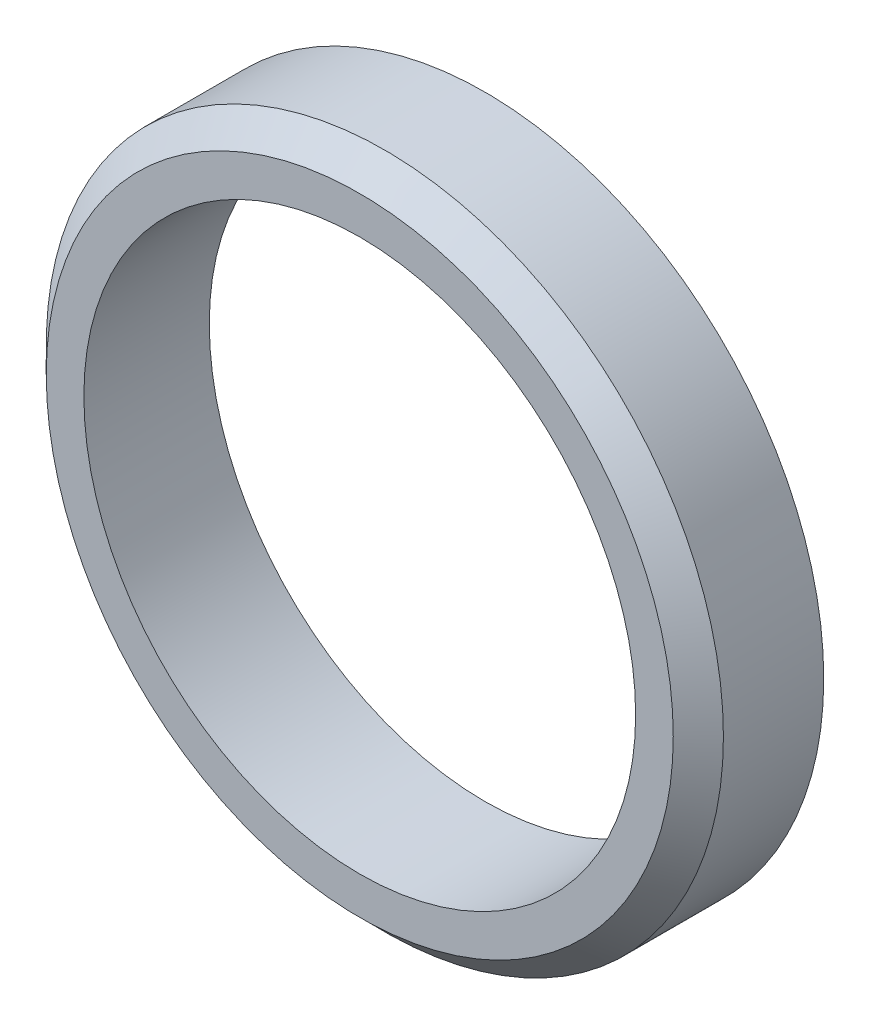
SolidWorks part; units mm, degrees
ref_plane "Спереди" through (0, 0, 0) normal (0, 0, 1) x (1, 0, 0)
ref_plane "Сверху" through (0, 0, 0) normal (0, 1, 0) x (1, 0, 0)
ref_plane "Справа" through (0, 0, 0) normal (1, 0, 0) x (0, 0, -1)
sketch "Эскиз1" plane through (0, 0, 0) normal (0, 0, 1) x (1, 0, 0)
  circle A0 centre (0, 0) radius 67.5
extrude "Бобышка-Вытянуть1" add sketch "Эскиз1" along normal blind 25
chamfer "Фаска1" distance 5 angle 45 1 edges at (67.5, 0, 25)
sketch "Эскиз2" plane through (0, 0, 0) normal (0, 0, -1) x (-1, 0, 0)
  circle A0 centre (0, 0) radius 55
extrude "Вырез-Вытянуть1" cut sketch "Эскиз2" against normal through all
